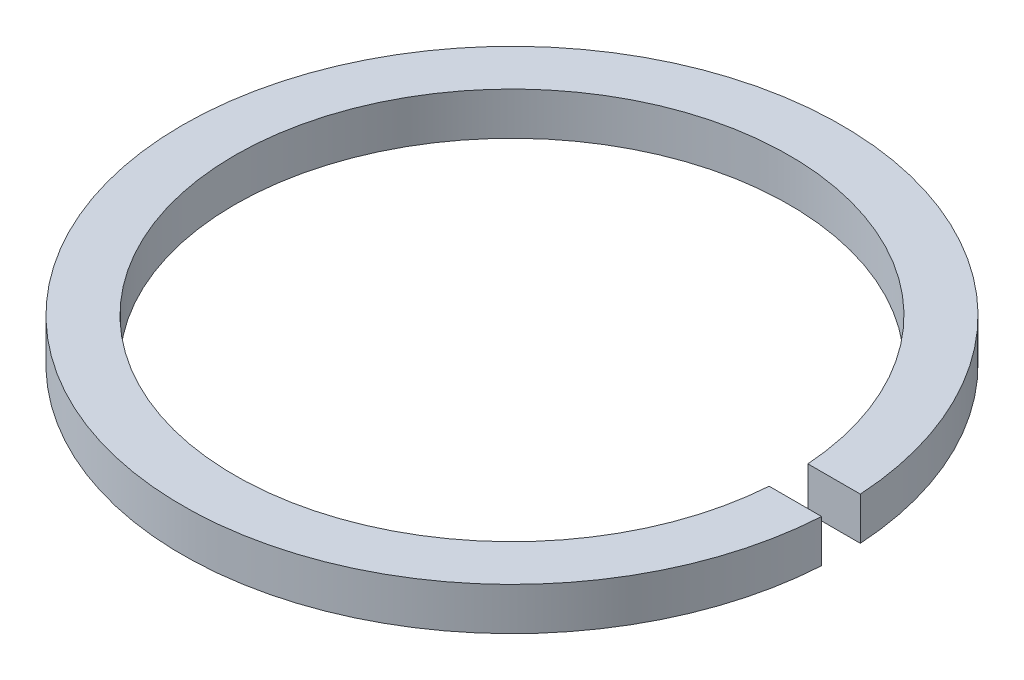
SolidWorks part; units mm, degrees
material "AISI 1020"
ref_plane "Front Plane" through (0, 0, 0) normal (0, 0, 1) x (1, 0, 0)
ref_plane "Top Plane" through (0, 0, 0) normal (0, 1, 0) x (1, 0, 0)
ref_plane "Right Plane" through (0, 0, 0) normal (1, 0, 0) x (0, 0, -1)
sketch "Sketch1" plane through (0, 0, 0) normal (0, 1, 0) x (1, 0, 0)
  line L1 (7.1325, 0.5) -> (10.5, 0.5)
  line L2 (7.1325, -0.5) -> (10.5, -0.5)
  line L3 (9.8995, 2.5) -> (10, 2.5)
  line L4 (9.8995, -2.5) -> (10, -2.5)
  line L5 (11, 1.5) -> (11, 1)
  line L6 (11, -1) -> (11, -1.5)
  line L7 (2.0562, 2.5) -> (20.5097, 2.5) construction
  line L8 (2.0562, 0.5) -> (20.5097, 0.5) construction
  arc A0 (7.1325, 0.5) -> (7.1325, -0.5) centre (0, 0) ccw
  arc A1 (8.9567, 3.1667) -> (8.9567, -3.1667) centre (0, 0) ccw
  arc A2 (10, 2.5) -> (11, 1.5) centre (10, 1.5) cw
  arc A3 (11, -1.5) -> (10, -2.5) centre (10, -1.5) cw
  arc A4 (8.9567, -3.1667) -> (9.8995, -2.5) centre (9.8995, -3.5) cw
  arc A5 (9.8995, 2.5) -> (8.9567, 3.1667) centre (9.8995, 3.5) cw
  circle A6 centre (10, 1.5) radius 0.5
  circle A7 centre (10, -1.5) radius 0.5
  arc A8 (10.5, -0.5) -> (11, -1) centre (10.5, -1) cw
  arc A9 (10.5, 0.5) -> (11, 1) centre (10.5, 1) ccw
  point P26 (11, -0.5)
  dimension "D1" = 14.3
  dimension "D2" = 19
  dimension "D3" = 1
  dimension "D6" = 1
  dimension "D7" = 0.5
  dimension "D5" = 11
  dimension "D4" = 2
extrude "Boss-Extrude1" add sketch "Sketch1" along normal blind 1.1
sketch "Sketch2" plane through (0, 1.1, 0) normal (0, 1, 0) x (1, 0, 0)
  circle A0 centre (0, 0) radius 8.5
  dimension "D1" = 17
extrude "Cut-Extrude1" cut sketch "Sketch2" against normal blind 10 flip side to cut
